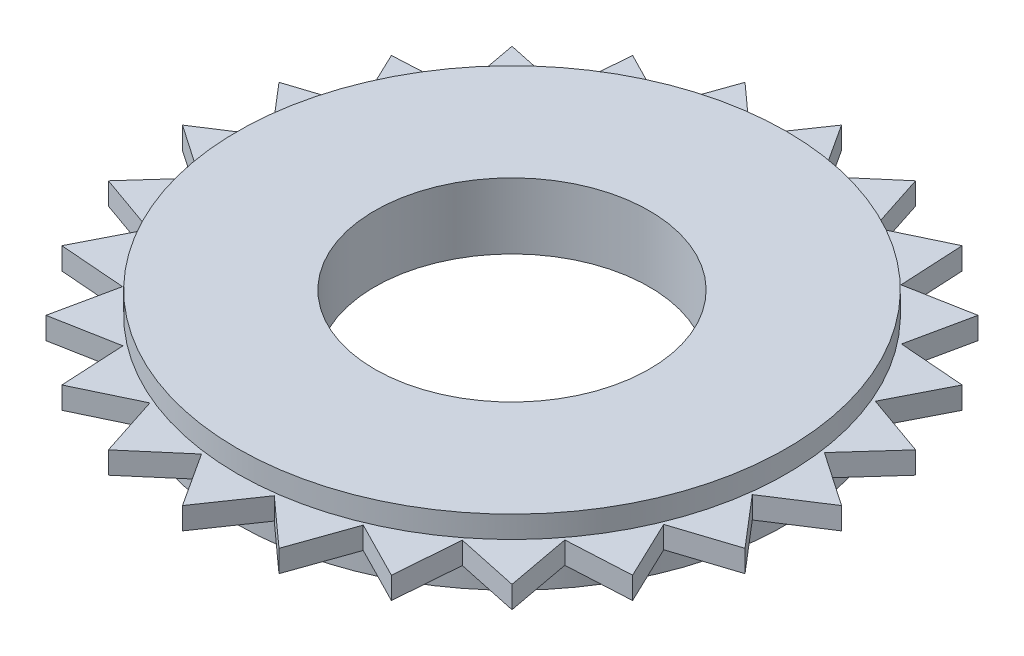
SolidWorks part; units mm, degrees
ref_plane "Front Plane" through (0, 0, 0) normal (0, 0, 1) x (1, 0, 0)
ref_plane "Top Plane" through (0, 0, 0) normal (0, 1, 0) x (1, 0, 0)
ref_plane "Right Plane" through (0, 0, 0) normal (1, 0, 0) x (0, 0, -1)
sketch "Sketch1" plane through (0, 0, 0) normal (0, 1, 0) x (1, 0, 0)
  circle A0 centre (0, 0) radius 12.5
  circle A1 centre (0, 0) radius 25
  dimension "D1" = 25
  dimension "D2" = 50
extrude "Boss-Extrude2" add sketch "Sketch1" along normal mid plane 6
sketch "Sketch4" plane through (0, 0, 0) normal (0, 1, 0) x (1, 0, 0)
  line L0 (0, 0) -> (0, 25) construction
  line L2 (0, 30) -> (-3.6124, 24.7376)
  line L4 (0, 30) -> (3.3948, 24.7684)
  line L7 (-3.6124, 24.7376) -> (0, 25)
  line L8 (0, 25) -> (3.3948, 24.7684)
  circle A0 centre (0, 0) radius 25 construction
  dimension "D2" = 7.0072
extrude "Boss-Extrude3" add sketch "Sketch4" along normal mid plane 2
pattern_circular "CirPattern1" count 24 over 360 about axis through (0, 0, 0) along (0, 1, 0) of "Boss-Extrude3"
